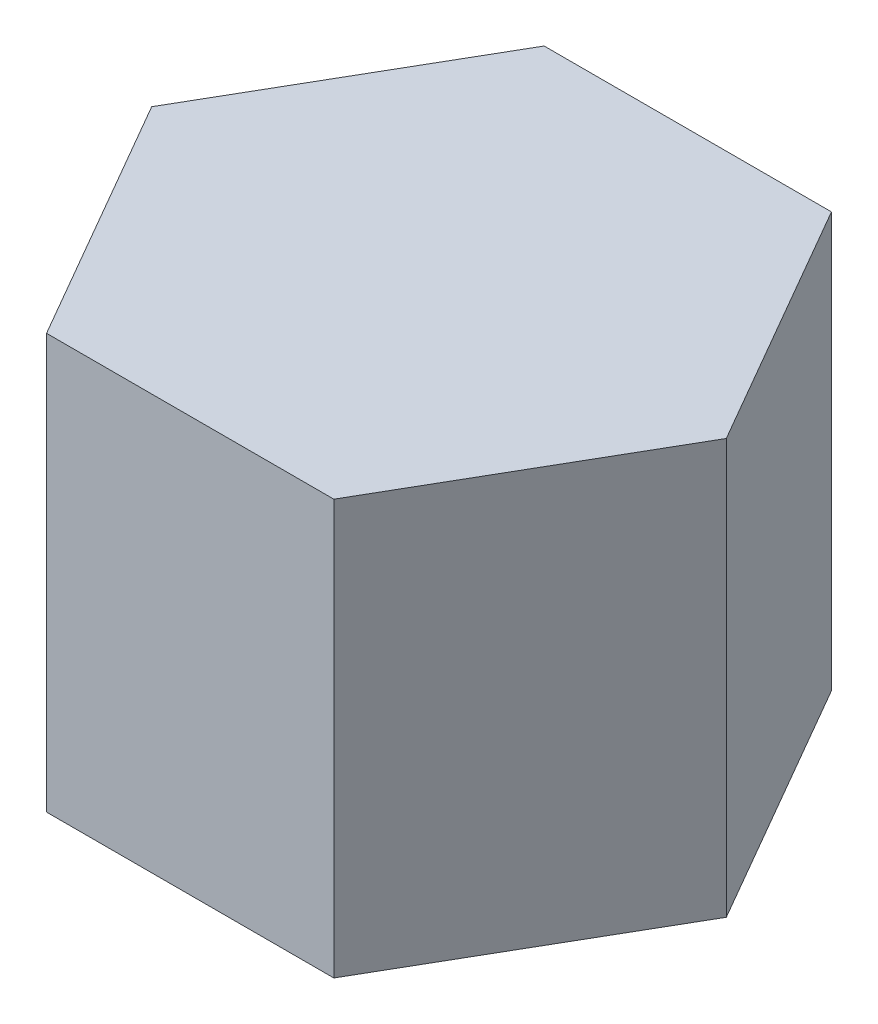
SolidWorks part; units mm, degrees
ref_plane "前视基准面" through (0, 0, 0) normal (0, 0, 1) x (1, 0, 0)
ref_plane "上视基准面" through (0, 0, 0) normal (0, 1, 0) x (1, 0, 0)
ref_plane "右视基准面" through (0, 0, 0) normal (1, 0, 0) x (0, 0, -1)
other "Configuration Table"
sketch "草图3" plane through (0, 0, 0) normal (0, 1, 0) x (1, 0, 0)
  line L7 (23.6603, 0) -> (6.3397, 0)
  line L8 (6.3397, 0) -> (-2.3205, -15)
  line L9 (-2.3205, -15) -> (6.3397, -30)
  line L10 (6.3397, -30) -> (23.6603, -30)
  line L11 (23.6603, -30) -> (32.3205, -15)
  line L12 (32.3205, -15) -> (23.6603, 0)
  circle A0 centre (15, -15) radius 15 construction
extrude "凸台-拉伸1" add sketch "草图3" along normal blind 25
